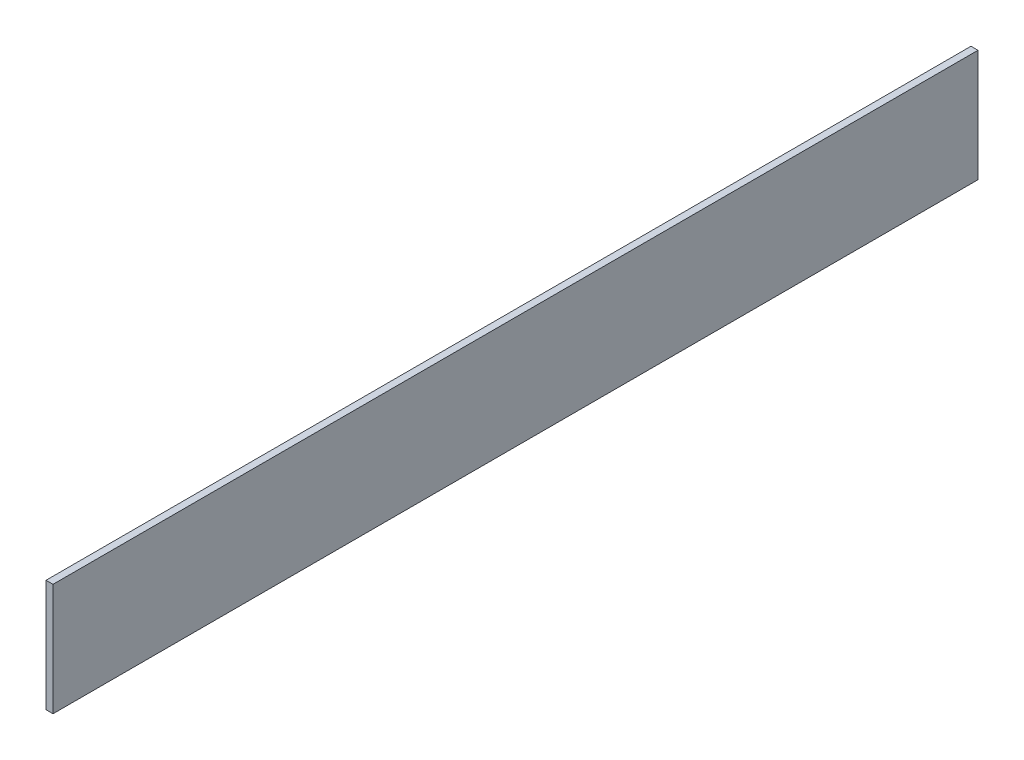
SolidWorks part; units mm, degrees
ref_plane "Front Plane" through (0, 0, 0) normal (0, 0, 1) x (1, 0, 0)
ref_plane "Top Plane" through (0, 0, 0) normal (0, 1, 0) x (1, 0, 0)
ref_plane "Right Plane" through (0, 0, 0) normal (1, 0, 0) x (0, 0, -1)
other "Configuration Table"
sketch "Sketch1" plane through (0, 0, 0) normal (0, 0, 1) x (1, 0, 0)
  line L1 (185, 552) -> (187.5, 552)
  line L2 (185, 552) -> (185, 592)
  line L3 (185, 592) -> (187.5, 592)
  line L4 (187.5, 552) -> (187.5, 592)
extrude "PACK_kalip_duvari_sol_1" add sketch "Sketch1" against normal blind 330 from offset 235 separate body
